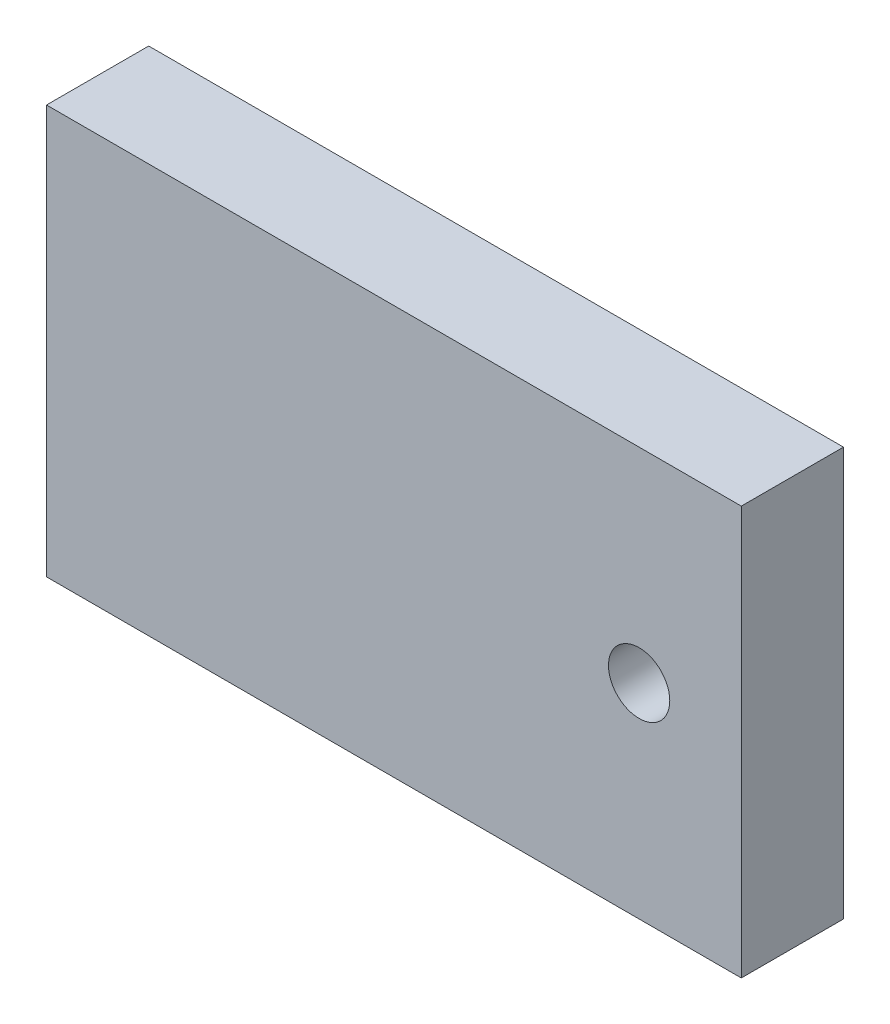
SolidWorks part; units mm, degrees
ref_plane "前视基准面" through (0, 0, 0) normal (0, 0, 1) x (1, 0, 0)
ref_plane "上视基准面" through (0, 0, 0) normal (0, 1, 0) x (1, 0, 0)
ref_plane "右视基准面" through (0, 0, 0) normal (1, 0, 0) x (0, 0, -1)
other "Configuration Table"
sketch "草图1" plane through (0, 0, 0) normal (0, 0, 1) x (1, 0, 0)
  line L5 (-29, -10) -> (5, -10)
  line L6 (-29, -10) -> (-29, 10)
  line L7 (-29, 10) -> (5, 10)
  line L8 (5, -10) -> (5, 10)
  circle A0 centre (0, 0) radius 1.5
  point P0 (3.2279, -2.6222)
  point P5 (0, 0)
  point P8 (0, 0)
  point P9 (5, 0)
  dimension "D4" = 34
  dimension "D1" = 3
  dimension "D3" = 20
extrude "凸台-拉伸1" add sketch "草图1" along normal blind 5 contours L5 L8 L7 L6 | A0
